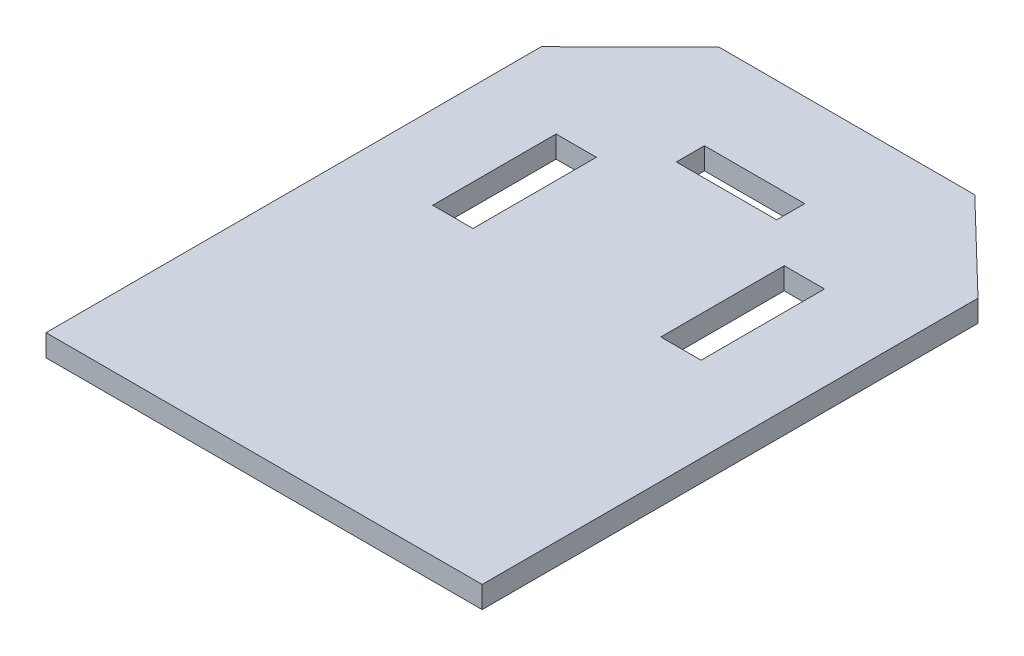
SolidWorks part; units mm, degrees
ref_plane "Front Plane" through (0, 0, 0) normal (0, 0, 1) x (1, 0, 0)
ref_plane "Top Plane" through (0, 0, 0) normal (0, 1, 0) x (1, 0, 0)
ref_plane "Right Plane" through (0, 0, 0) normal (1, 0, 0) x (0, 0, -1)
sketch "Sketch1" plane through (0, 0, 0) normal (0, 1, 0) x (1, 0, 0)
  line L0 (-89.5122, 32.3329) -> (-89.5122, -81.3655)
  line L1 (-89.5122, -81.3655) -> (10.4878, -81.3655)
  line L2 (4.2175, 38.2162) -> (-5.6459, 48.0795)
  line L3 (-89.5122, 32.3329) -> (-84.6439, 36.8554)
  line L4 (-74.8405, 46.6588) -> (-68.9105, 52.5888)
  line L5 (-89.5122, -26.3781) -> (-61.1732, -26.3781) construction
  line L6 (-32.7344, 52.59) -> (-46.6834, 38.7259) construction
  line L7 (10.4878, 32.3329) -> (10.4878, -81.3655)
  line L8 (-32.7344, 52.59) -> (-46.6834, 52.59)
  line L9 (-46.6834, 52.59) -> (-46.6834, 38.7259)
  line L10 (-69.1312, 45.1077) -> (-83.0802, 31.2437) construction
  line L11 (10.4878, 32.3329) -> (11.0537, 32.1973)
  line L12 (-10.409, 52.49) -> (-69.0093, 52.49)
  line L13 (10.4878, 32.3329) -> (-10.409, 52.49)
  line L14 (-69.1312, 31.2437) -> (-83.0802, 45.1077) construction
  line L15 (4.2175, 38.2162) -> (-5.5859, 28.4128)
  line L16 (-5.5859, 28.4128) -> (-15.4493, 38.2762)
  line L17 (-5.6459, 48.0795) -> (-15.4493, 38.2762)
  line L18 (4.2175, 38.2162) -> (-15.4493, 38.2762) construction
  line L19 (-5.5859, 28.4128) -> (-5.6459, 48.0795) construction
  line L20 (-64.9771, 36.7954) -> (-74.8405, 46.6588)
  line L21 (-64.9771, 36.7954) -> (-74.7805, 26.992)
  line L22 (-74.7805, 26.992) -> (-84.6439, 36.8554)
  line L23 (-74.8405, 46.6588) -> (-84.6439, 36.8554)
  line L24 (-64.9771, 36.7954) -> (-84.6439, 36.8554) construction
  line L25 (-32.7344, 52.59) -> (-32.7344, 38.7259)
  line L26 (-29.8757, 45.7541) -> (-49.5425, 45.6941) construction
  line L27 (-39.7001, 55.467) -> (-39.7601, 35.8002) construction
  line L28 (-32.7344, 38.7259) -> (-46.6834, 38.7259)
  line L29 (-39.7091, 52.49) -> (-39.7091, -47.6671) construction
  line L30 (10.4878, 23.4935) -> (-3.4611, 9.6294) construction
  line L31 (10.4878, 23.4935) -> (-3.4611, 23.4935)
  line L32 (-3.4611, 23.4935) -> (-3.4611, 9.6294)
  line L33 (10.4878, 23.4935) -> (10.4878, 9.6294)
  line L34 (10.4878, 9.6294) -> (-3.4611, 9.6294)
  line L35 (-75.5633, 23.4935) -> (-89.5122, 9.6294) construction
  line L36 (-75.5633, 23.4935) -> (-89.5122, 23.4935)
  line L37 (-89.5122, 23.4935) -> (-89.5122, 9.6294)
  line L38 (-75.5633, 23.4935) -> (-75.5633, 9.6294)
  line L39 (-75.5633, 9.6294) -> (-89.5122, 9.6294)
  line L40 (-89.5122, 32.3329) -> (-69.0093, 52.49)
  line L41 (-61.1732, -26.3781) -> (-61.1732, 52.49) construction
  line L42 (-49.8091, -11.7386) -> (-29.6091, -11.7386)
  line L43 (-49.8091, -11.7386) -> (-49.8091, 16.5614)
  line L44 (-49.8091, 16.5614) -> (-29.6091, 16.5614)
  line L45 (-29.6091, -11.7386) -> (-29.6091, 16.5614)
  line L46 (-49.8091, -11.7386) -> (-29.6091, 16.5614) construction
  line L47 (-49.8091, 16.5614) -> (-29.6091, -11.7386) construction
  line L48 (-18.1732, -58.0433) -> (-61.1732, -58.0433)
  line L49 (-18.1732, -58.0433) -> (-18.1732, -15.0433)
  line L50 (-18.1732, -15.0433) -> (-61.1732, -15.0433)
  line L51 (-61.1732, -58.0433) -> (-61.1732, -15.0433)
  line L52 (-18.1732, -58.0433) -> (-61.1732, -15.0433) construction
  line L53 (-18.1732, -15.0433) -> (-61.1732, -58.0433) construction
  line L54 (-61.1732, 52.49) -> (-61.1732, -58.0433) construction
  line L55 (-66.0122, -81.3655) -> (-66.0122, -63.3655)
  line L56 (-66.0122, -81.3655) -> (-13.0122, -81.3655)
  line L57 (-13.0122, -81.3655) -> (-13.0122, -63.3655)
  line L58 (-66.0122, -63.3655) -> (-13.0122, -63.3655)
  line L59 (-66.0122, -81.3655) -> (-13.0122, -63.3655) construction
  line L60 (-13.0122, -81.3655) -> (-66.0122, -63.3655) construction
  line L61 (-18.1732, -15.0433) -> (-18.1732, 52.49) construction
  line L62 (-70.4831, -11.7386) -> (-61.245, -11.7386)
  line L63 (-87.2833, -61.6633) -> (-87.2833, -54.4233)
  line L64 (-87.2833, -61.6633) -> (-63.8433, -61.6633)
  line L65 (-63.8433, -61.6633) -> (-63.8433, -54.4233)
  line L66 (-87.2833, -54.4233) -> (-63.8433, -54.4233)
  line L67 (-87.2833, -61.6633) -> (-63.8433, -54.4233) construction
  line L68 (-63.8433, -61.6633) -> (-87.2833, -54.4233) construction
  line L69 (-51.1456, 31.2437) -> (-28.1504, 31.2437)
  line L70 (-51.1456, 31.2437) -> (-51.1456, 24.7965)
  line L71 (-51.1456, 24.7965) -> (-28.1504, 24.7965)
  line L72 (-28.1504, 31.2437) -> (-28.1504, 24.7965)
  line L73 (-8.9351, 16.5614) -> (-18.1732, 16.5614)
  line L74 (-8.9351, 16.5614) -> (-8.9351, -11.7386)
  line L75 (-8.9351, -11.7386) -> (-18.1732, -11.7386)
  line L76 (-18.1732, 16.5614) -> (-18.1732, -11.7386)
  line L77 (-61.245, 16.5614) -> (-61.245, -11.7386)
  line L78 (-70.4831, 16.5614) -> (-61.245, 16.5614)
  line L79 (-70.4831, 16.5614) -> (-70.4831, -11.7386)
  point P2 (-76.1057, 38.1757)
  point P9 (-40.129, 70.6619)
  point P11 (-5.6159, 38.2462)
  point P18 (-74.8105, 36.8254)
  point P24 (-39.7089, 45.658)
  point P30 (-39.7089, 45.658)
  point P37 (3.5133, 16.5614)
  point P38 (3.5133, 16.5614)
  point P43 (-82.5377, 16.5614)
  point P44 (-82.5377, 16.5614)
  point P50 (-39.7091, 2.4114)
  point P55 (-39.6732, -36.5433)
  point P61 (-39.5122, -72.3655)
  point P66 (-75.5633, -58.0433)
  dimension "D1" = 18
  dimension "D2" = 53
  dimension "D3" = 100
  dimension "D4" = 20.2
  dimension "D5" = 28.3
  dimension "D6" = 43
  dimension "D7" = 43
  dimension "D8" = 7.24
  dimension "D9" = 23.44
  dimension "D10" = 113.6984
  dimension "D11" = 133.8555
  dimension "D12" = 29.0342
extrude "Boss-Extrude1" add sketch "Sketch1" along normal blind 5 contours L55 L58 L57 L1 L7 L34 L32 L31 L13 L2 L15 L16 L17 L12 L25 L28 L9 L4 L20 L21 L22 L3 L0 L36 L38 L39 L79 L78 L77 L62 L76 L73 L74 L75 L45 L42 L43 L44 L48 L51 L50 L49 | L58 L55 L1 L57 | L66 L63 L64 L65 | L34 L7 L31 L32 | L13 L17 L16 L15 L2 | L28 L25 L12 L9 | L20 L23 L22 L21 | L39 L38 L36 L0 | L42 L45 L44 L43 | L51 L48 L49 L50
sketch "Sketch2" plane through (0, 5, 0) normal (0, 1, 0) x (1, 0, 0)
  line L0 (10.4878, 32.3329) -> (10.4878, -81.3655) construction
  line L1 (-65.5946, -23.6453) -> (-13.8751, -23.6453)
  line L2 (-65.5946, -23.6453) -> (-65.5946, -67.6144)
  line L3 (-65.5946, -67.6144) -> (-13.8751, -67.6144)
  line L4 (-13.8751, -23.6453) -> (-13.8751, -67.6144)
  line L5 (-51.8295, 14.1237) -> (-29.2246, 14.1237)
  line L6 (-51.8295, 14.1237) -> (-51.8295, -9.055)
  line L7 (-51.8295, -9.055) -> (-29.2246, -9.055)
  line L8 (-29.2246, 14.1237) -> (-29.2246, -9.055)
  line L9 (10.4878, -13.9565) -> (-9.424, -13.9565)
  line L10 (10.4878, -13.9565) -> (10.4878, -35.1634)
  line L11 (10.4878, -35.1634) -> (-9.424, -35.1634)
  line L12 (-9.424, -13.9565) -> (-9.424, -35.1634)
  line L13 (-10.409, 52.49) -> (-69.0093, 52.49) construction
  line L14 (-89.5122, -81.3655) -> (10.4878, -81.3655) construction
  line L15 (-39.7091, 52.49) -> (-39.5122, -81.3655) construction
  line L16 (-89.7103, -14.1039) -> (-89.6479, -35.3107)
  line L17 (-89.7103, -14.1039) -> (-69.7986, -14.0453)
  line L18 (-69.7986, -14.0453) -> (-69.7362, -35.2521)
  line L19 (-89.6479, -35.3107) -> (-69.7362, -35.2521)
